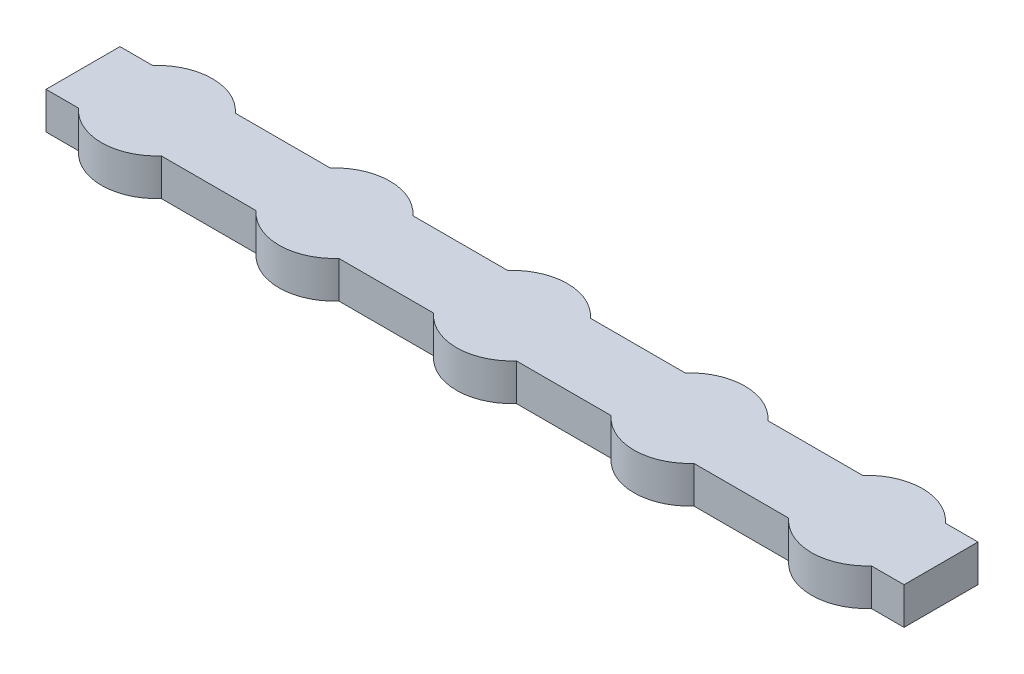
SolidWorks part; units mm, degrees
ref_plane "Plan de face" through (0, 0, 0) normal (0, 0, 1) x (1, 0, 0)
ref_plane "Plan de dessus" through (0, 0, 0) normal (0, 1, 0) x (1, 0, 0)
ref_plane "Plan de droite" through (0, 0, 0) normal (1, 0, 0) x (0, 0, -1)
sketch "Esquisse1" plane through (0, 0, 0) normal (0, 0, 1) x (1, 0, 0)
  line L1 (-58, 5) -> (58, 5)
  line L2 (-58, 5) -> (-58, 0)
  line L3 (-58, 0) -> (58, 0)
  line L4 (58, 5) -> (58, 0)
  point P4 (0, 0)
  dimension "D1" = 5
  dimension "D2" = 116
extrude "Boss.-Extru.1" add sketch "Esquisse1" along normal blind 10
sketch "Esquisse3" plane through (0, 0, 0) normal (0, 1, 0) x (1, 0, 0)
  line L0 (-48, 0) -> (-48, -10) construction
  line L1 (58, 0) -> (-58, 0) construction
  line L2 (58, -10) -> (-58, -10) construction
  line L3 (-58, -10) -> (-58, 0) construction
  line L4 (-36, 0) -> (-36, -10) construction
  line L5 (-12, 0) -> (-12, -10) construction
  line L6 (12, 0) -> (12, -10) construction
  line L7 (36, 0) -> (36, -10) construction
  line L8 (60, 0) -> (60, -10) construction
  circle A0 centre (-48, -5) radius 7.5
  circle A1 centre (-24, -5) radius 7.5
  circle A2 centre (0, -5) radius 7.5
  circle A3 centre (24, -5) radius 7.5
  circle A4 centre (48, -5) radius 7.5
  dimension "D2" = 15
  dimension "D1" = 10
  dimension "D3" = 12
  dimension "D4" = 12
  dimension "D5" = 24
extrude "Boss.-Extru.3" add sketch "Esquisse3" along normal blind 5
